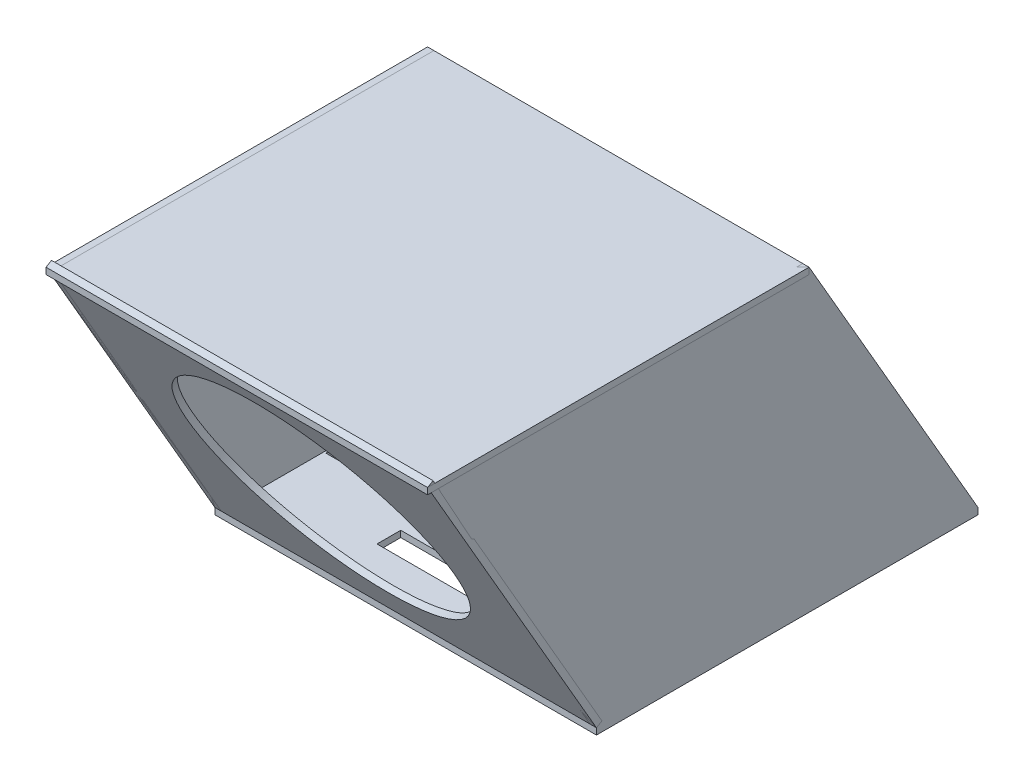
SolidWorks part; units mm, degrees
ref_plane "Front Plane" through (0, 0, 0) normal (0, 0, 1) x (1, 0, 0)
ref_plane "Top Plane" through (0, 0, 0) normal (0, 1, 0) x (1, 0, 0)
ref_plane "Right Plane" through (0, 0, 0) normal (1, 0, 0) x (0, 0, -1)
sketch "Sketch1" plane through (0, 0, 0) normal (0, 1, 0) x (1, 0, 0)
  line L1 (-30, -30) -> (30, -30)
  line L2 (-30, -30) -> (-30, 30)
  line L3 (-30, 30) -> (30, 30)
  line L4 (30, -30) -> (30, 30)
  line L5 (-30, -30) -> (30, 30) construction
  line L6 (-30, 30) -> (30, -30) construction
  point P0 (0, 0)
  dimension "D1" = 60
  dimension "D2" = 60
extrude "Boss-Extrude1" add sketch "Sketch1" along normal blind 1
sketch "Sketch2" plane through (-30, 0, 0) normal (-1, 0, 0) x (0, 0, 1)
  line L0 (-30, 1) -> (30, 1)
  line L1 (-30, 1) -> (-3.4419, 47)
  line L2 (30, 1) -> (56.5581, 47)
  line L3 (-3.4419, 47) -> (56.5581, 47)
  line L4 (-30, 1) -> (-30, 12.0768) construction
  dimension "D1" = 46
  dimension "D2" = 30
extrude "Boss-Extrude2" add sketch "Sketch2" against normal blind 1
sketch "Sketch3" plane through (30, 0, 0) normal (1, 0, 0) x (0, 0, -1)
  line L0 (30, 1) -> (-30, 1)
  line L1 (30, 1) -> (3.4419, 47)
  line L2 (-30, 1) -> (-56.5581, 47)
  line L3 (3.4419, 47) -> (-56.5581, 47)
extrude "Boss-Extrude3" add sketch "Sketch3" against normal blind 1
ref_plane "Plane1" through (0, 13.2404, -22.933) normal (0, 0.5, -0.866) x (-1, 0, 0)
sketch "Sketch5" plane through (0, 13.2404, -22.933) normal (0, 0.5, -0.866) x (-1, 0, 0)
  line L0 (-30, -15) -> (30, -15) construction
  line L1 (-29, 38.9823) -> (30, 38.9823)
  line L2 (-29, 38.9823) -> (-29, -15)
  line L3 (-29, -15) -> (30, -15)
  line L4 (30, 38.9823) -> (30, -15)
extrude "Boss-Extrude4" add sketch "Sketch5" against normal blind 1
sketch "Sketch6" plane through (0, 0, 0) normal (0, -1, 0) x (1, 0, 0)
  line L0 (-30, -29.4226) -> (30, 30) construction
  line L1 (30, 30) -> (30, -30) construction
  line L2 (30, -30) -> (-30, 30) construction
  line L3 (0, 0) -> (15.6623, 0) construction
  line L4 (-12.284, 22.2246) -> (12.284, 22.2246)
  line L5 (-12.284, 22.2246) -> (-12.284, 18.4901)
  line L6 (-12.284, 18.4901) -> (12.284, 18.4901)
  line L7 (12.284, 22.2246) -> (12.284, 18.4901)
  line L8 (-12.284, 22.2246) -> (12.284, 18.4901) construction
  line L9 (-12.284, 18.4901) -> (12.284, 22.2246) construction
  line L10 (12.284, -22.2246) -> (12.284, -18.4901)
  line L11 (-12.284, -22.2246) -> (-12.284, -18.4901)
  line L12 (-12.284, -22.2246) -> (12.284, -22.2246)
  line L13 (-12.284, -18.4901) -> (12.284, -18.4901)
  line L14 (0, 0) -> (0, 13.8774) construction
  line L15 (28.6663, 13.8774) -> (25.2552, 13.8774)
  line L20 (-28.6663, -13.8774) -> (-25.2552, -13.8774)
  line L21 (-28.6663, -13.8774) -> (-28.6663, 13.8774)
  line L22 (-28.6663, 13.8774) -> (-25.2552, 13.8774)
  line L23 (-25.2552, -13.8774) -> (-25.2552, 13.8774)
  line L24 (-28.6663, -13.8774) -> (-25.2552, 13.8774) construction
  line L25 (-28.6663, 13.8774) -> (-25.2552, -13.8774) construction
  line L26 (25.2552, -13.8774) -> (25.2552, 13.8774)
  line L27 (28.6663, -13.8774) -> (25.2552, -13.8774)
  line L28 (28.6663, -13.8774) -> (28.6663, 13.8774)
  line L29 (28.6663, 13.8774) -> (25.2552, -13.8774) construction
  line L30 (28.6663, -13.8774) -> (25.2552, 13.8774) construction
  point P8 (0, 20.3573)
  point P19 (-26.9607, 0)
  point P29 (26.9607, 0)
extrude "Cut-Extrude2" cut sketch "Sketch6" against normal blind 1
sketch "Sketch9" plane through (0, 13.2404, -22.933) normal (0, 0.5, -0.866) x (-1, 0, 0)
  line L0 (-30, -14.567) -> (30, 38.9823) construction
  line L1 (-30, -14.134) -> (-30, -15) construction
  line L2 (30, 38.9823) -> (30, -15) construction
  line L3 (30, -15) -> (-30, 38.9823) construction
  circle A0 centre (0, 12.2076) radius 21
extrude "Cut-Extrude3" cut sketch "Sketch9" against normal blind 1
ref_plane "Plane3" through (0, 0, 130) normal (0, 0, 1) x (1, 0, 0)
ref_plane "Plane4" through (0, -12.9596, 22.4467) normal (0, 0.5, -0.866) x (-1, 0, 0)
sketch "Sketch13" plane through (0, -12.7404, 22.067) normal (0, -0.5, 0.866) x (1, 0, 0)
  line L1 (-30, 68.9823) -> (30, 68.9823)
  line L2 (-30, 68.9823) -> (-30, 15.866)
  line L3 (-30, 15.866) -> (30, 15.866)
  line L4 (30, 68.9823) -> (30, 15.866)
extrude "Boss-Extrude6" add sketch "Sketch13" against normal blind 1 separate body
sketch "Sketch14" plane through (0, -12.7404, 22.067) normal (0, -0.5, 0.866) x (1, 0, 0)
  line L0 (-30, 15.866) -> (30, 68.9823) construction
  line L1 (30, 68.9823) -> (30, 15.866) construction
  line L2 (30, 15.866) -> (-30, 68.9823) construction
  circle A0 centre (0, 42.4241) radius 21
extrude "Cut-Extrude4" cut sketch "Sketch14" against normal blind 1
sketch "Sketch15" plane through (0, 47, 0) normal (0, 1, 0) x (1, 0, 0)
  line L1 (-30, 3.4419) -> (30, 3.4419)
  line L2 (-30, 3.4419) -> (-30, -56.5581)
  line L3 (-30, -56.5581) -> (30, -56.5581)
  line L4 (30, 3.4419) -> (30, -56.5581)
extrude "Boss-Extrude7" add sketch "Sketch15" against normal blind 1 separate body
